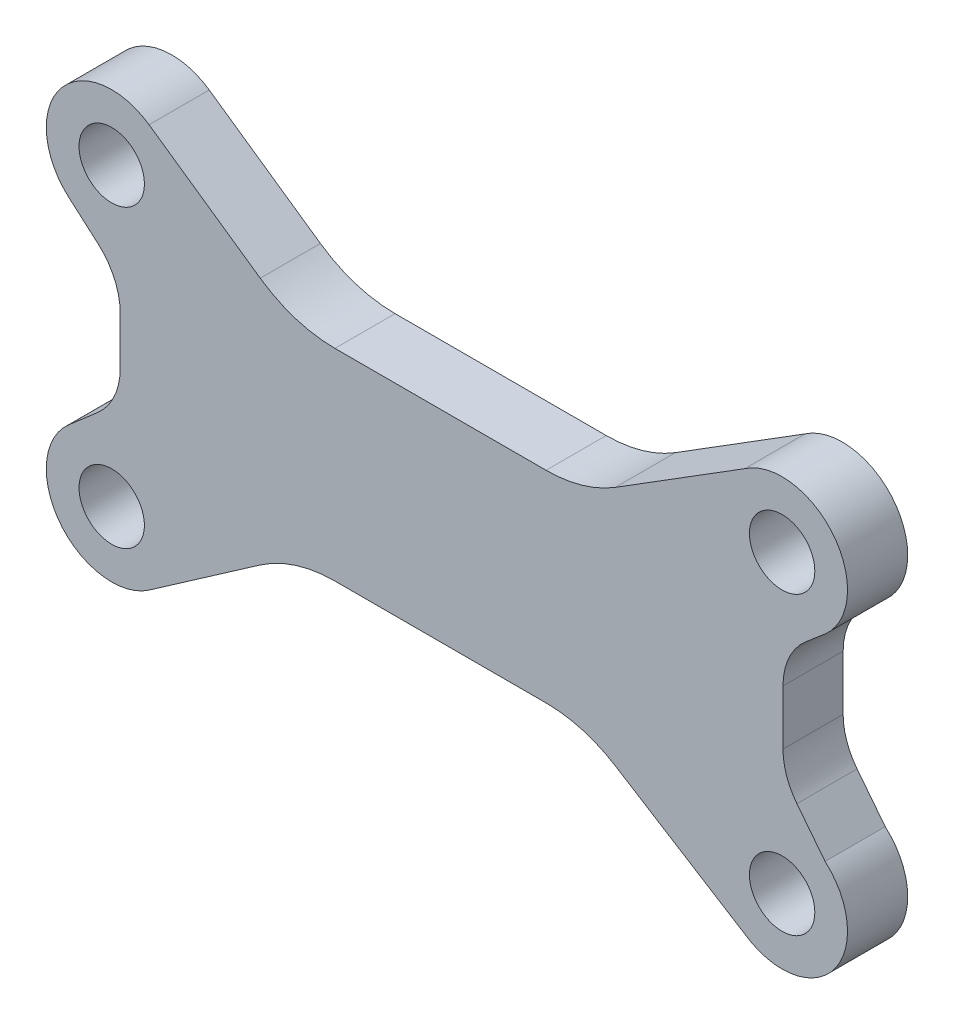
SolidWorks part; units mm, degrees
ref_plane "Front Plane" through (0, 0, 0) normal (0, 0, 1) x (1, 0, 0)
ref_plane "Top Plane" through (0, 0, 0) normal (0, 1, 0) x (1, 0, 0)
ref_plane "Right Plane" through (0, 0, 0) normal (1, 0, 0) x (0, 0, -1)
sketch "Sketch1" plane through (0, 0, 0) normal (0, 0, 1) x (1, 0, 0)
  line L0 (-18.8232, 25.0598) -> (-18.8232, -3.6422) construction
  line L1 (46.2643, -3.6422) -> (46.2643, 25.0598) construction
  line L2 (46.2643, 10.7088) -> (-18.8232, 10.7088) construction
  line L3 (-17.9973, 15.9183) -> (-22.9945, 20.272)
  line L4 (-1.1351, 20.4907) -> (-15.197, 30.2726)
  line L5 (13.7205, 10.7088) -> (13.7205, 0) construction
  line L6 (26.9887, 20.4907) -> (42.6381, 30.2726)
  line L7 (46.3486, 16.7986) -> (50.4356, 20.272)
  line L8 (-1.1351, 20.4907) -> (26.9887, 20.4907)
  line L9 (46.3486, 6.3633) -> (50.4356, 1.1456)
  line L10 (-17.9973, 5.483) -> (-22.9945, 1.1456)
  line L11 (-17.9973, 15.9183) -> (-17.9973, 5.483)
  line L12 (46.3486, 16.7986) -> (46.3486, 6.3633)
  line L16 (26.9887, 0.9269) -> (42.6381, -8.855)
  line L17 (-1.1351, 0.9269) -> (-15.197, -8.855)
  line L18 (-1.1351, 0.9269) -> (26.9887, 0.9269)
  circle A0 centre (-18.8232, 25.0598) radius 3.175
  circle A1 centre (46.2643, 25.0598) radius 3.175
  arc A2 (-15.197, 30.2726) -> (-22.9945, 20.272) centre (-18.8232, 25.0598) ccw
  arc A3 (50.4356, 20.272) -> (42.6381, 30.2726) centre (46.2643, 25.0598) ccw
  arc A4 (52.6143, -3.6422) -> (50.4356, 1.1456) centre (46.2643, -3.6422) ccw
  circle A5 centre (46.2643, -3.6422) radius 3.175
  circle A6 centre (-18.8232, -3.6422) radius 3.175
  arc A7 (-22.9945, 1.1456) -> (-25.1732, -3.6422) centre (-18.8232, -3.6422) ccw
  arc A8 (-22.9945, 1.1456) -> (-15.197, -8.855) centre (-18.8232, -3.6422) ccw
  arc A9 (42.6381, -8.855) -> (50.4356, 1.1456) centre (46.2643, -3.6422) ccw
  dimension "D1" = 6.35
  dimension "D4" = 12.7
  dimension "D3" = 2
  dimension "D6" = 28.702
  dimension "D7" = 65.0875
  dimension "D2" = 2
  dimension "D5" = 2
extrude "Boss-Extrude1" add sketch "Sketch1" along normal blind 5.842 contours L16 A9 A4 L9 L12 L7 A3 L6 L8 L4 A2 L3 L11 L10 A7 A8 L17 L18 A0 A1 A5 A6
fillet "Fillet1" radius 6.35 4 edges at (-17.9973, 15.9183, 2.921) (-17.9973, 5.483, 2.921) (46.3486, 16.7986, 2.921) (46.3486, 6.3633, 2.921)
fillet "Fillet2" radius 12.7 4 edges at (26.9887, 20.4907, 2.921) (-1.1351, 20.4907, 2.921) (26.9887, 0.9269, 2.921) (-1.1351, 0.9269, 2.921)
